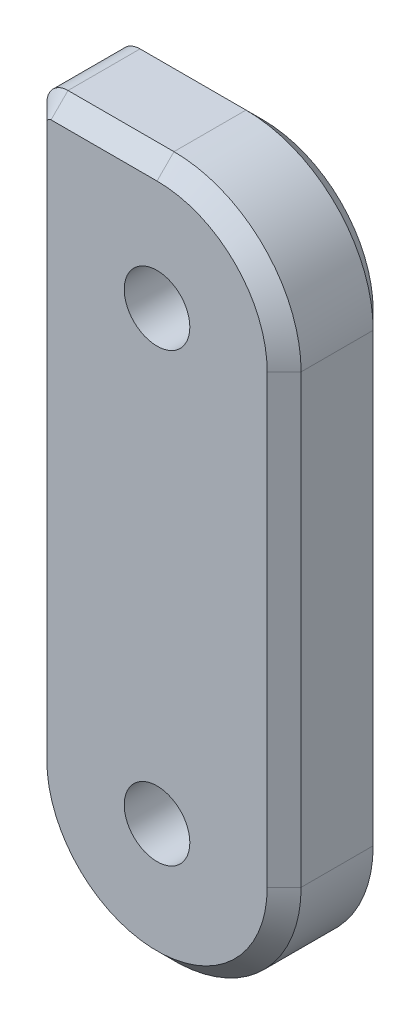
SolidWorks part; units mm, degrees
material "PET"
ref_plane "Front Plane" through (0, 0, 0) normal (0, 0, 1) x (1, 0, 0)
ref_plane "Top Plane" through (0, 0, 0) normal (0, 1, 0) x (1, 0, 0)
ref_plane "Right Plane" through (0, 0, 0) normal (1, 0, 0) x (0, 0, -1)
sketch "Sketch2" plane through (0, 0, 0) normal (0, 0, 1) x (1, 0, 0)
  line L0 (0, -218.6158) -> (0, -202.8355) construction
  line L1 (-9.525, 42.9692) -> (-9.525, 0)
  line L2 (9.525, 33.4442) -> (9.525, 0)
  line L4 (-9.525, 42.9692) -> (0, 42.9692)
  arc A0 (-9.525, 0) -> (9.525, 0) centre (0, 0) ccw
  arc A1 (9.525, 33.4442) -> (0, 42.9692) centre (0, 33.4442) ccw
  point P1 (-9.525, 42.9692)
  point P10 (-9.525, 42.4662)
  dimension "D1" = 19.05
  dimension "D3" = 19.05
  dimension "D2" = 33.4442
extrude "Boss-Extrude1" add sketch "Sketch2" along normal blind 7.9375
hole_wizard "#8 Clearance Hole1" positions "Sketch3" profile "Sketch4" hole size "#8" standard "ANSI Inch" end condition up to next
sketch "Sketch3" plane through (0, 0, 7.9375) normal (0, 0, 1) x (1, 0, 0)
  point P0 (0, 0)
sketch "Sketch4" plane through (0, 0, 7.9375) normal (1, 0, 0) x (0, -1, 0)
  line L0 (0, 0) -> (0, 7.9375)
  line L1 (0, 7.9375) -> (2.4574, 7.9375)
  line L2 (2.4574, 7.9375) -> (2.4574, 0)
  line L5 (2.4574, 0) -> (0, 0)
  line L11 (0, -6.35) -> (0, 107.95) construction
  dimension "Thru Hole Dia." = 4.9149
  dimension "Thru Hole Depth" = 7.9375
hole_wizard "#8 Clearance Hole2" positions "Sketch5" profile "Sketch6" hole size "#8" standard "ANSI Inch" end condition up to next
sketch "Sketch5" plane through (0, 0, 7.9375) normal (0, 0, 1) x (1, 0, 0)
  point P0 (0, 33.4442)
sketch "Sketch6" plane through (0, 33.4442, 7.9375) normal (1, 0, 0) x (0, -1, 0)
  line L0 (0, 0) -> (0, 7.9375)
  line L1 (0, 7.9375) -> (2.4574, 7.9375)
  line L2 (2.4574, 7.9375) -> (2.4574, 0)
  line L5 (2.4574, 0) -> (0, 0)
  line L11 (0, -6.35) -> (0, 107.95) construction
  dimension "Thru Hole Dia." = 4.9149
  dimension "Thru Hole Depth" = 7.9375
sketch "Sketch7" plane through (0, 0, 0) normal (0, 0, -1) x (-1, 0, 0)
  circle A0 centre (0, 33.4442) radius 9.525 construction
  circle A1 centre (0, 33.4442) radius 5.08
  dimension "D1" = 19.05
  dimension "D2" = 10.16
extrude "Cut-Extrude1" cut sketch "Sketch7" against normal blind 2.032
fillet "Fillet1" radius 1.5875 1 edges at (-9.525, 42.9692, 3.9688)
chamfer "Chamfer2" distance 1.27 angle 45 12 edges at (6.7352, 40.1794, 0) (-3.9688, 42.9692, 0) (9.525, 16.7221, 0) (-9.06, 42.5042, 0) (0, -9.525, 0) (-9.525, 20.6908, 0) (6.7352, 40.1794, 7.9375) (-3.9688, 42.9692, 7.9375) (9.525, 16.7221, 7.9375) (-9.06, 42.5042, 7.9375) (0, -9.525, 7.9375) (-9.525, 20.6908, 7.9375)
